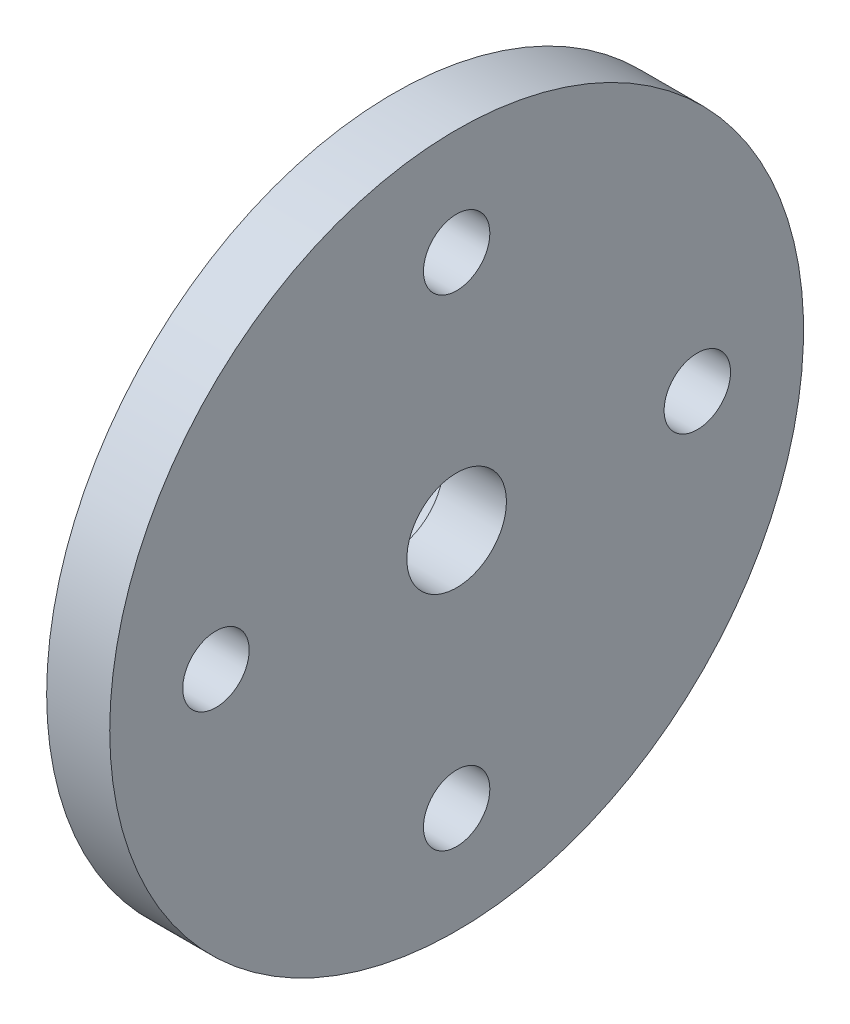
SolidWorks part; units mm, degrees
ref_plane "Front Plane" through (0, 0, 0) normal (0, 0, 1) x (1, 0, 0)
ref_plane "Top Plane" through (0, 0, 0) normal (0, 1, 0) x (1, 0, 0)
ref_plane "Right Plane" through (0, 0, 0) normal (1, 0, 0) x (0, 0, -1)
sketch "Sketch1" plane through (0, 0, 0) normal (1, 0, 0) x (0, 0, -1)
  circle A0 centre (0, 0) radius 4.4
  circle A1 centre (0, 0) radius 3
extrude "Boss-Extrude1" add sketch "Sketch1" along normal blind 3.5
sketch "Sketch2" plane through (3.5, 0, 0) normal (1, 0, 0) x (0, 0, -1)
  circle A0 centre (0, 0) radius 10.45
extrude "Boss-Extrude2" add sketch "Sketch2" along normal blind 1.9
sketch "Sketch3" plane through (5.4, 0, 0) normal (1, 0, 0) x (0, 0, -1)
  circle A0 centre (0, 0) radius 1.5
extrude "Cut-Extrude1" cut sketch "Sketch3" against normal blind 1.9
sketch "Sketch4" plane through (5.4, 0, 0) normal (1, 0, 0) x (0, 0, -1)
  line L0 (0, 0) -> (13.2349, 0) construction
  line L1 (0, 0) -> (0, 11.0244) construction
  circle A0 centre (0, 7.25) radius 1
  circle A1 centre (7.25, 0) radius 1
  circle A2 centre (0, -7.25) radius 1
  circle A3 centre (-7.25, 0) radius 1
  point P17 (0, 0)
  dimension "D1" = 7.25
  dimension "D2" = 4
extrude "Cut-Extrude2" cut sketch "Sketch4" against normal up to vertex (5.4 mm away) up to point (0, 0, 0)
